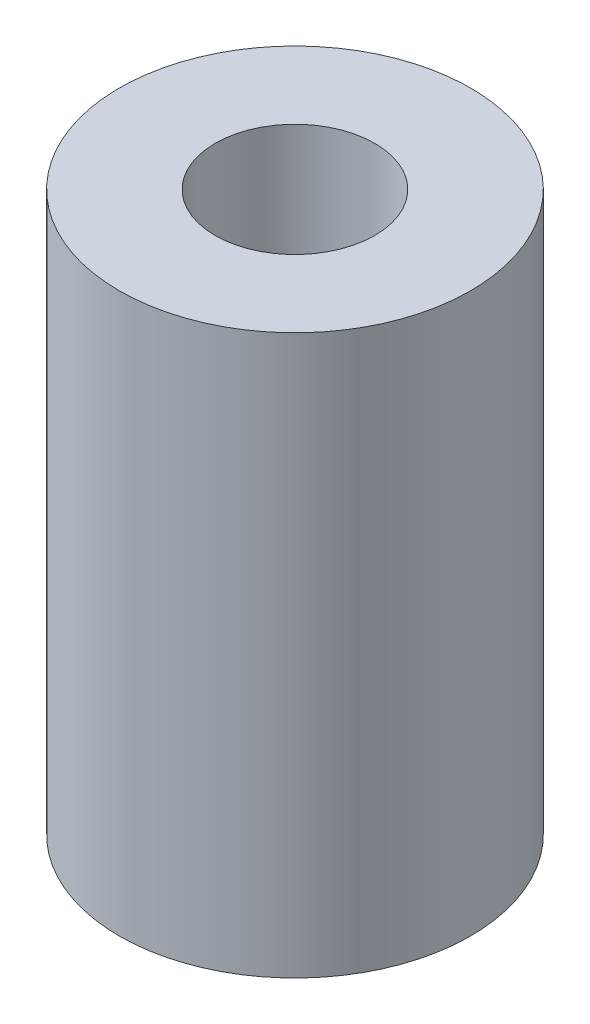
SolidWorks part; units mm, degrees
ref_plane "Front Plane" through (0, 0, 0) normal (0, 0, 1) x (1, 0, 0)
ref_plane "Top Plane" through (0, 0, 0) normal (0, 1, 0) x (1, 0, 0)
ref_plane "Right Plane" through (0, 0, 0) normal (1, 0, 0) x (0, 0, -1)
sketch "Sketch1" plane through (0, 0, 0) normal (0, 1, 0) x (1, 0, 0)
  circle A0 centre (0, 0) radius 2.5
  circle A1 centre (0, 0) radius 5.5
  dimension "D1" = 11
  dimension "D2" = 5
extrude "Boss-Extrude1" add sketch "Sketch1" along normal blind 17.5
